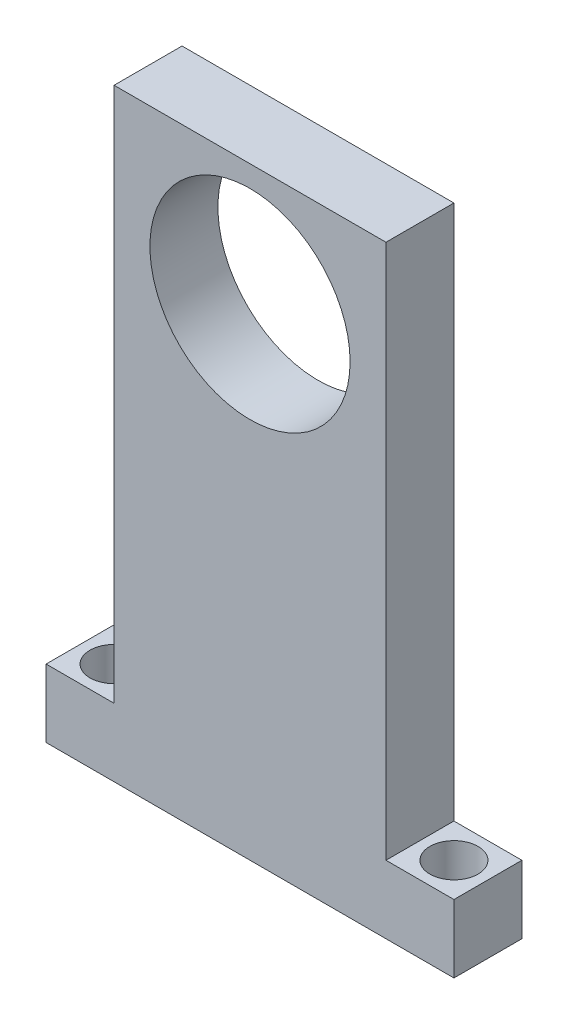
SolidWorks part; units mm, degrees
ref_plane "Front Plane" through (0, 0, 0) normal (0, 0, 1) x (1, 0, 0)
ref_plane "Top Plane" through (0, 0, 0) normal (0, 1, 0) x (1, 0, 0)
ref_plane "Right Plane" through (0, 0, 0) normal (1, 0, 0) x (0, 0, -1)
sketch "Sketch1" plane through (0, 0, 0) normal (0, 1, 0) x (1, 0, 0)
  line L1 (-19.05, -3.175) -> (19.05, -3.175)
  line L2 (-19.05, -3.175) -> (-19.05, 3.175)
  line L3 (-19.05, 3.175) -> (19.05, 3.175)
  line L4 (19.05, -3.175) -> (19.05, 3.175)
  line L5 (-19.05, -3.175) -> (19.05, 3.175) construction
  line L6 (-19.05, 3.175) -> (19.05, -3.175) construction
  point P0 (0, 0)
  dimension "D1" = 38.1
  dimension "D2" = 6.35
extrude "Boss-Extrude1" add sketch "Sketch1" along normal blind 6.35
sketch "Sketch3" plane through (0, 6.35, 0) normal (0, 1, 0) x (1, 0, 0)
  line L0 (19.05, 3.175) -> (-19.05, 3.175) construction
  line L1 (-12.7, -3.175) -> (12.7, -3.175)
  line L2 (-12.7, -3.175) -> (-12.7, 3.175)
  line L3 (-12.7, 3.175) -> (12.7, 3.175)
  line L4 (12.7, -3.175) -> (12.7, 3.175)
  line L5 (-12.7, -3.175) -> (12.7, 3.175) construction
  line L6 (-12.7, 3.175) -> (12.7, -3.175) construction
  point P0 (0, 0)
  dimension "D1" = 25.4
extrude "Boss-Extrude2" add sketch "Sketch3" along normal blind 50
sketch "Sketch4" plane through (0, 6.35, 0) normal (0, 1, 0) x (1, 0, 0)
  line L0 (-12.7, 3.175) -> (-19.05, 3.175) construction
  circle A0 centre (-15.875, 0) radius 2.2479
  circle A1 centre (15.875, 0) radius 2.2479
  point P4 (-15.875, 3.175)
  dimension "D1" = 4.4958
  dimension "D2" = 4.4958
sketch "Sketch6" plane through (0, 0, 3.175) normal (0, 0, 1) x (1, 0, 0)
  circle A0 centre (0, 45) radius 9.35
  dimension "D1" = 18.7
  dimension "D2" = 45
extrude "Cut-Extrude3" cut sketch "Sketch6" against normal through all
extrude "Cut-Extrude1" cut sketch "Sketch4" against normal through all
sketch "Sketch5" plane through (0, 0, 3.175) normal (0, 0, 1) x (1, 0, 0)
  circle A0 centre (0, 45.2568) radius 9.017
  dimension "D1" = 18.034
extrude "Cut-Extrude2" cut sketch "Sketch5" against normal through all
